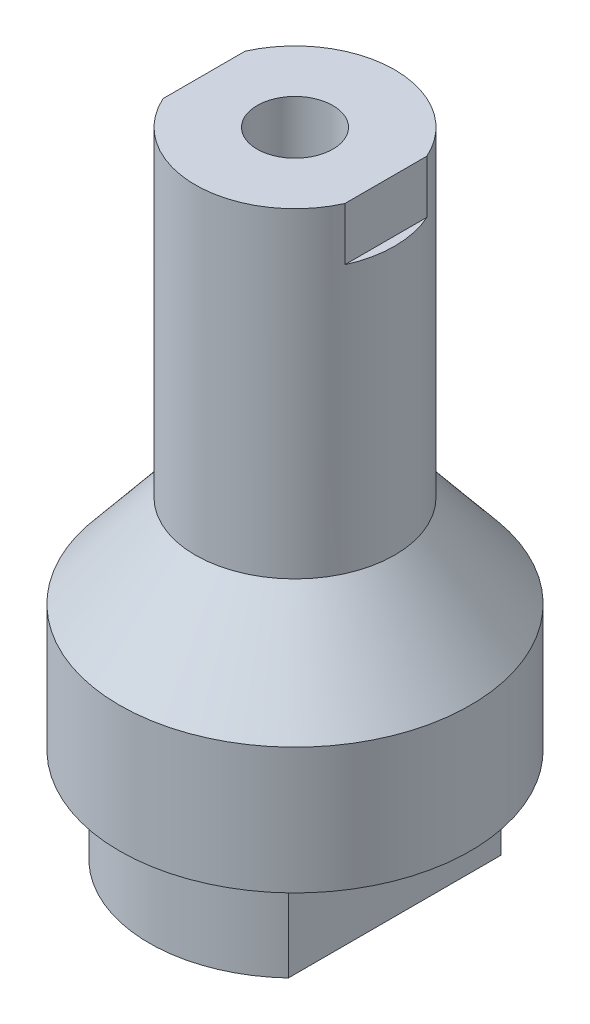
SolidWorks part; units mm, degrees
ref_plane "Plano frontal" through (0, 0, 0) normal (0, 0, 1) x (1, 0, 0)
ref_plane "Plano superior" through (0, 0, 0) normal (0, 1, 0) x (1, 0, 0)
ref_plane "Plano direito" through (0, 0, 0) normal (1, 0, 0) x (0, 0, -1)
sketch "Esboço1" plane through (0, 0, 0) normal (0, 0, 1) x (1, 0, 0)
  line L0 (-5.775, 0) -> (-5.775, 3.75)
  line L1 (-5.775, 0) -> (0, 0)
  line L2 (-6.95, 3.75) -> (-6.95, 8.75)
  line L3 (-3.95, 25.1) -> (0, 25.1)
  line L4 (0, 0) -> (0, 25.1) construction
  line L5 (-5.775, 3.75) -> (-6.95, 3.75)
  line L6 (-6.95, 8.75) -> (-3.95, 12.4)
  line L7 (-3.95, 12.4) -> (-3.95, 25.1)
  line L8 (0, 25.1) -> (0, 0)
  point P0 (5.5536, -0.7812)
  dimension "D1" = 11.55
  dimension "D2" = 7.9
  dimension "D3" = 25.1
  dimension "D4" = 13.9
  dimension "D5" = 3.75
  dimension "D6" = 5
  dimension "D7" = 12.7
revolve "Revolução1" add sketch "Esboço1" angle 360 about L4
sketch "Esboço2" plane through (0, 0, 0) normal (0, 0, 1) x (1, 0, 0)
  line L0 (0, 25.1) -> (0, 0) construction
  line L1 (3.95, 25.1) -> (-3.95, 25.1) construction
  line L2 (-5.775, 0) -> (5.775, 0) construction
  line L3 (-5.775, 0) -> (-3.95, 0)
  line L4 (-5.775, 0) -> (-5.775, 3.75)
  line L5 (-5.775, 3.75) -> (-3.95, 3.75)
  line L6 (-3.95, 0) -> (-3.95, 3.75)
  line L7 (-5.775, 3.75) -> (5.775, 3.75) construction
  line L8 (-5.775, 3.75) -> (-5.775, 0) construction
  line L9 (-3.95, 25.1) -> (-3.6, 25.1)
  line L10 (-3.95, 25.1) -> (-3.95, 23)
  line L11 (-3.95, 23) -> (-3.6, 23)
  line L12 (-3.6, 25.1) -> (-3.6, 23)
  line L13 (3.6, 25.1) -> (3.6, 23)
  line L14 (3.95, 23) -> (3.6, 23)
  line L15 (3.95, 25.1) -> (3.95, 23)
  line L16 (3.95, 25.1) -> (3.6, 25.1)
  line L17 (3.95, 0) -> (3.95, 3.75)
  line L18 (5.775, 3.75) -> (3.95, 3.75)
  line L19 (5.775, 0) -> (5.775, 3.75)
  line L20 (5.775, 0) -> (3.95, 0)
  point P18 (-2.5411, 3.75)
  dimension "D1" = 7.2
  dimension "D2" = 2.1
  dimension "D3" = 7.9
extrude "Corte-extrusão1" cut sketch "Esboço2" against normal through all both and the other way through all
sketch "Esboço3" plane through (0, 0, 0) normal (0, 1, 0) x (1, 0, 0)
  circle A0 centre (0, 0) radius 1.5
  dimension "D1" = 3
extrude "Corte-extrusão2" cut sketch "Esboço3" along normal through all both and the other way through all
